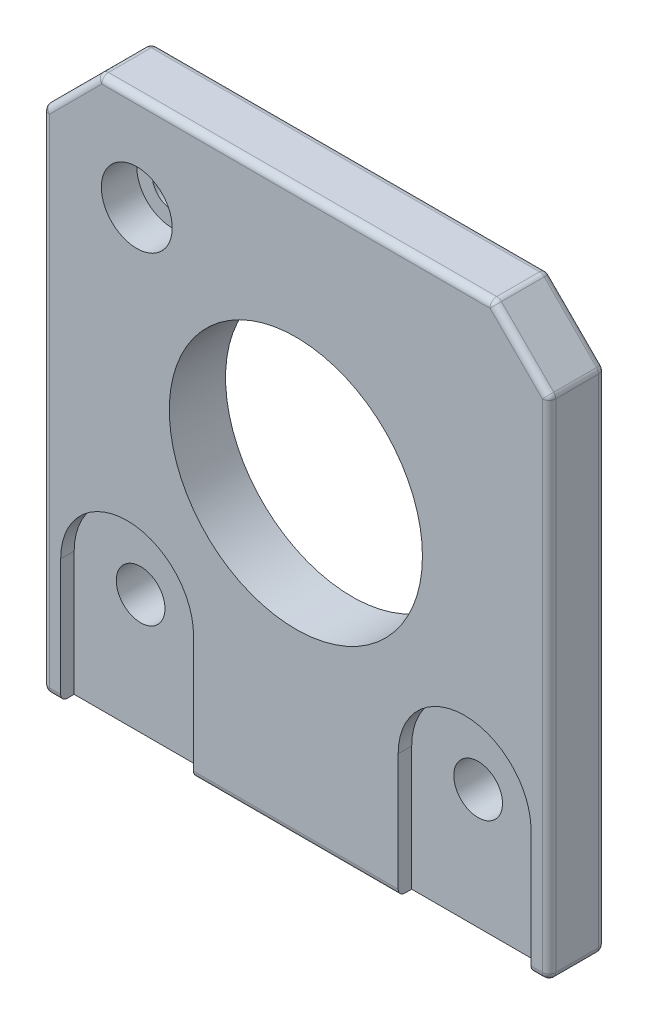
SolidWorks part; units mm, degrees
ref_plane "Front Plane" through (0, 0, 0) normal (0, 0, 1) x (1, 0, 0)
ref_plane "Top Plane" through (0, 0, 0) normal (0, 1, 0) x (1, 0, 0)
ref_plane "Right Plane" through (0, 0, 0) normal (1, 0, 0) x (0, 0, -1)
sketch "Sketch2" plane through (0, 0, 0) normal (0, 1, 0) x (1, 0, 0)
  line L1 (-28.575, 3.175) -> (28.575, 3.175)
  line L2 (-28.575, 3.175) -> (-28.575, -3.175)
  line L3 (-28.575, -3.175) -> (28.575, -3.175)
  line L4 (28.575, 3.175) -> (28.575, -3.175)
  point P4 (0, 3.175)
  point P7 (-28.575, 0)
  dimension "D1" = 6.35
  dimension "D2" = 57.15
extrude "Boss-Extrude1" add sketch "Sketch2" against normal blind 63.5
sketch "Sketch3" plane through (0, 0, 3.175) normal (0, 0, 1) x (1, 0, 0)
  line L2 (-28.575, 0) -> (28.575, 0) construction
  circle A0 centre (0, -28.815) radius 14.2875
  point P2 (0, 0)
  dimension "D1" = 28.815
  dimension "D3" = 28.575
extrude "Cut-Extrude1" cut sketch "Sketch3" against normal through all
chamfer "Chamfer1" distance 6.35 angle 45 2 edges at (-28.575, 0, 0) (28.575, 0, 0)
hole_wizard "M5 Clearance Hole1" positions "Sketch6" profile "Sketch7" hole size "M5" standard "ANSI Metric" end condition through all
sketch "Sketch6" plane through (0, 0, 3.175) normal (0, 0, 1) x (1, 0, 0)
  line L0 (-28.575, -63.5) -> (28.575, -63.5) construction
  line L1 (28.575, -63.5) -> (28.575, -6.35) construction
  point P0 (-19.05, -50)
  point P3 (19.05, -50)
  dimension "D1" = 13.5
  dimension "D2" = 9.525
  dimension "D3" = 38.1
sketch "Sketch7" plane through (-19.05, -50, 3.175) normal (1, 0, 0) x (0, -1, 0)
  line L0 (0, 0) -> (0, 6.35)
  line L1 (0, 6.35) -> (2.75, 6.35)
  line L2 (2.75, 6.35) -> (2.75, 0)
  line L5 (2.75, 0) -> (0, 0)
  line L11 (0, -6.35) -> (0, 107.95) construction
  dimension "Thru Hole Dia." = 5.5
  dimension "Thru Hole Depth" = 6.35
fillet "Fillet1" radius 0.762 18 edges at (0, -63.5, 3.175) (0, -63.5, -3.175) (28.575, -63.5, 0) (28.575, -34.925, 3.175) (28.575, -34.925, -3.175) (-28.575, -63.5, 0) (-28.575, -34.925, -3.175) (-28.575, -34.925, 3.175) (-25.4, -3.175, 3.175) (-28.575, -6.35, 0) (-25.4, -3.175, -3.175) (0, 0, 3.175) (-22.225, 0, 0) (0, 0, -3.175) (22.225, 0, 0) (25.4, -3.175, -3.175) (28.575, -6.35, 0) (25.4, -3.175, 3.175)
sketch "Sketch8" plane through (0, 0, 3.175) normal (0, 0, 1) x (1, 0, 0)
  line L0 (11.55, -63.5) -> (11.55, -49.5)
  line L1 (26.55, -49.5) -> (26.55, -63.5)
  line L2 (11.55, -63.5) -> (26.55, -63.5)
  arc A0 (11.55, -49.5) -> (26.55, -49.5) centre (19.05, -49.5) cw
extrude "Cut-Extrude4" cut sketch "Sketch8" against normal blind 1.524
mirror "Mirror1" about plane through (0, 0, 0) normal (1, 0, 0) of "Cut-Extrude4"
hole_wizard "CBORE for M4 SHCS2" positions "Sketch9" profile "Sketch10" counterbore size "M4" standard "ANSI Metric" end condition through all
sketch "Sketch9" plane through (0, 0, 3.175) normal (0, 0, 1) x (1, 0, 0)
  line L0 (-21.9094, 0) -> (21.9094, 0) construction
  line L1 (-28.575, -62.738) -> (-28.575, -6.6656) construction
  point P0 (-17.9605, -10.8545)
  dimension "D1" = 10.8545
  dimension "D2" = 10.6145
sketch "Sketch10" plane through (-17.9605, -10.8545, 3.175) normal (1, 0, 0) x (0, -1, 0)
  line L0 (0, 0) -> (0, 6.35)
  line L1 (0, 6.35) -> (2.25, 6.35)
  line L3 (2.25, 6.35) -> (2.25, 4)
  line L4 (2.25, 4) -> (4, 4)
  line L5 (4, 4) -> (4, 0)
  line L7 (4, 0) -> (0, 0)
  line L11 (0, -6.35) -> (0, 107.95) construction
  dimension "Thru Hole Dia." = 4.5
  dimension "Thru Hole Depth" = 6.35
  dimension "C'Bore Dia." = 8
  dimension "C'Bore Depth" = 4
